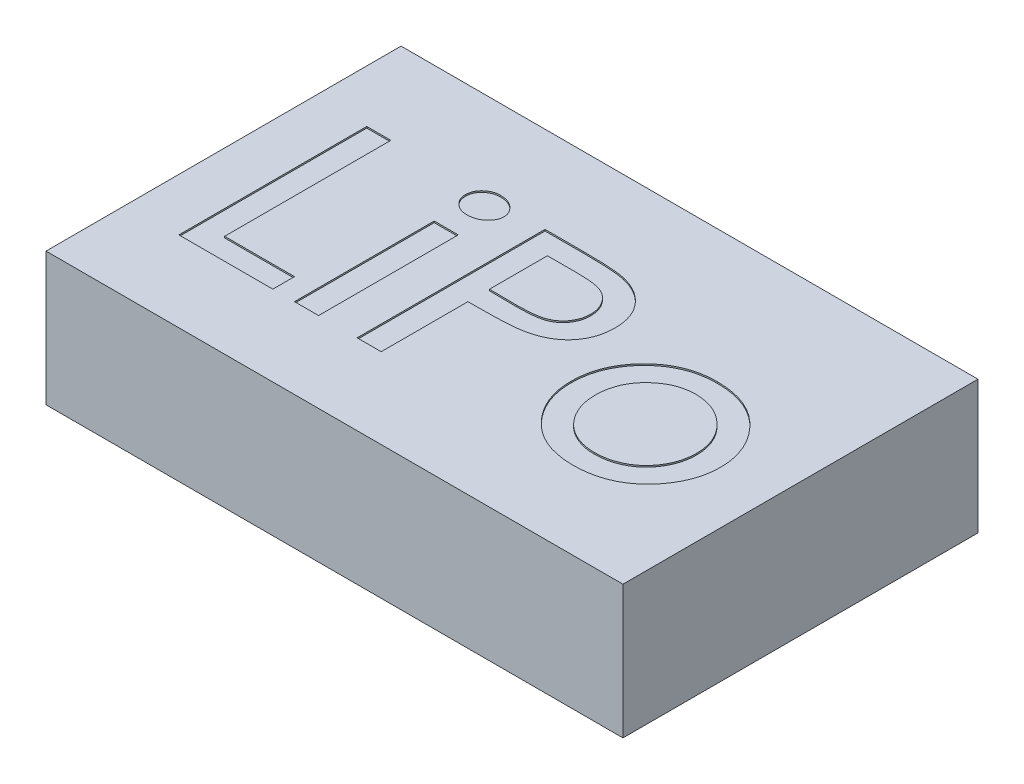
SolidWorks part; units mm, degrees
ref_plane "Front Plane" through (0, 0, 0) normal (0, 0, 1) x (1, 0, 0)
ref_plane "Top Plane" through (0, 0, 0) normal (0, 1, 0) x (1, 0, 0)
ref_plane "Right Plane" through (0, 0, 0) normal (1, 0, 0) x (0, 0, -1)
sketch "Sketch1" plane through (0, 0, 0) normal (0, 1, 0) x (1, 0, 0)
  line L1 (19.5, -12) -> (-19.5, -12)
  line L2 (19.5, -12) -> (19.5, 12)
  line L3 (19.5, 12) -> (-19.5, 12)
  line L4 (-19.5, -12) -> (-19.5, 12)
  line L5 (19.5, -12) -> (-19.5, 12) construction
  line L6 (19.5, 12) -> (-19.5, -12) construction
  point P0 (0, 0)
  dimension "D1" = 39
  dimension "D2" = 24
extrude "Boss-Extrude1" add sketch "Sketch1" along normal blind 9
sketch "Sketch2" plane through (0, 9, 0) normal (0, 1, 0) x (1, 0, 0)
  text T0 "<b>LiPo</b>" font "Century Gothic" height in points 48
extrude "Cut-Extrude1" cut sketch "Sketch2" against normal blind 0.1
